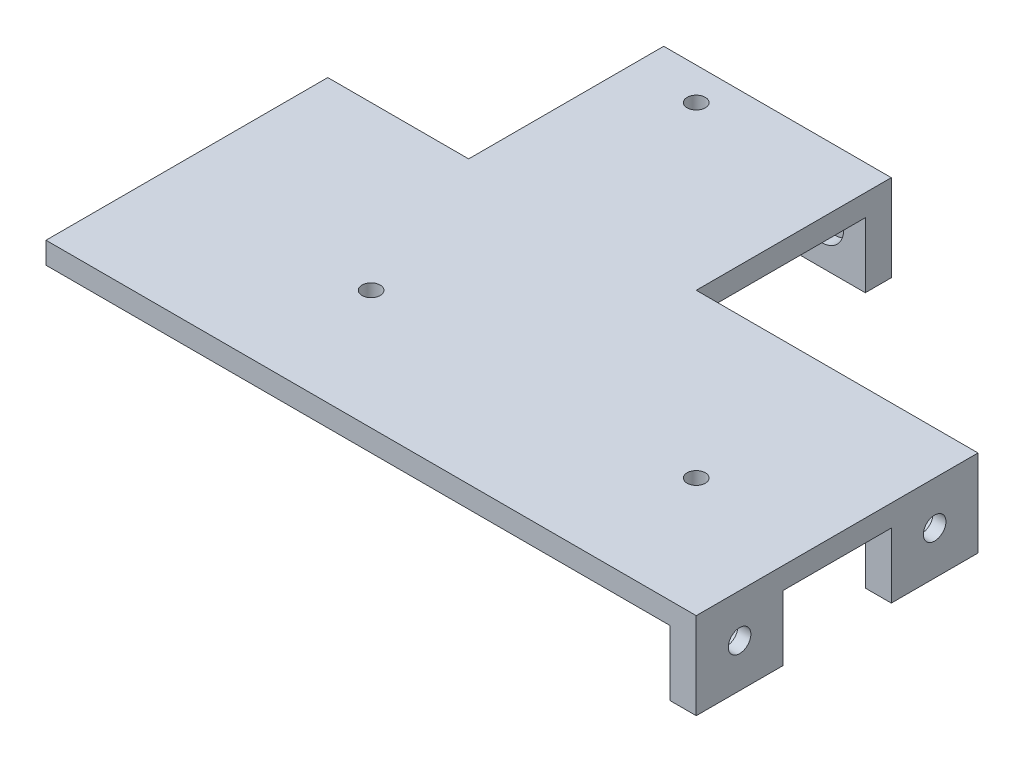
SolidWorks part; units mm, degrees
ref_plane "前视基准面" through (0, 0, 0) normal (0, 0, 1) x (1, 0, 0)
ref_plane "上视基准面" through (0, 0, 0) normal (0, 1, 0) x (1, 0, 0)
ref_plane "右视基准面" through (0, 0, 0) normal (1, 0, 0) x (0, 0, -1)
other "Configuration Table"
sketch "草图1" plane through (0, 0, 0) normal (0, 1, 0) x (1, 0, 0)
  line L6 (0, -65) -> (0, -130)
  line L7 (32.5, -65) -> (0, -65)
  line L15 (32.5, -20) -> (32.5, -65)
  line L18 (150, -130) -> (0, -130)
  line L20 (85, -20) -> (85, -65)
  line L21 (85, -20) -> (32.5, -20)
  line L24 (85, -65) -> (150, -65)
  line L25 (150, -65) -> (150, -130)
  circle A0 centre (47.5, -27.5) radius 2.1
  circle A2 centre (47.5, -102.5) radius 2.1
  circle A3 centre (122.5, -102.5) radius 2.1
extrude "凸台-拉伸1" add sketch "草图1" along normal blind 5
sketch "草图2" plane through (150, 0, 0) normal (1, 0, 0) x (0, 0, -1)
  line L1 (-65, 5) -> (-85, 5)
  line L2 (-65, 5) -> (-65, -15)
  line L3 (-65, -15) -> (-85, -15)
  line L4 (-85, 5) -> (-85, -15)
  circle A0 centre (-75, -5) radius 2.6
extrude "凸台-拉伸2" add sketch "草图2" against normal blind 6
sketch "草图3" plane through (144, 0, 0) normal (-1, 0, 0) x (0, 0, 1)
  circle A0 centre (75, -5) radius 5
extrude "切除-拉伸1" cut sketch "草图3" against normal blind 3
sketch "草图5" plane through (0, 0, 20) normal (0, 0, -1) x (-1, 0, 0)
  line L1 (-85, 5) -> (-65, 5)
  line L2 (-85, 5) -> (-85, -15)
  line L3 (-85, -15) -> (-65, -15)
  line L4 (-65, 5) -> (-65, -15)
  circle A0 centre (-75, -5) radius 2.6
extrude "凸台-拉伸3" add sketch "草图5" against normal blind 6
sketch "草图6" plane through (0, 0, 26) normal (0, 0, 1) x (1, 0, 0)
  circle A0 centre (75, -5) radius 5
extrude "切除-拉伸2" cut sketch "草图6" against normal blind 3
sketch "草图7" plane through (150, 0, 0) normal (1, 0, 0) x (0, 0, -1)
  line L1 (-130, 5) -> (-110, 5)
  line L2 (-130, 5) -> (-130, -15)
  line L3 (-130, -15) -> (-110, -15)
  line L4 (-110, 5) -> (-110, -15)
  circle A0 centre (-120, -5) radius 2.6
extrude "凸台-拉伸4" add sketch "草图7" against normal blind 6
sketch "草图8" plane through (144, 0, 0) normal (-1, 0, 0) x (0, 0, 1)
  circle A0 centre (120, -5) radius 5
extrude "切除-拉伸3" cut sketch "草图8" against normal blind 3
sketch "草图9" plane through (0, 0, 0) normal (0, -1, 0) x (1, 0, 0)
  circle A0 centre (47.5, 102.5) radius 5
  circle A1 centre (122.5, 102.5) radius 5
  circle A2 centre (47.5, 27.5) radius 5
  circle A3 centre (47.5, 102.5) radius 2.1
  circle A4 centre (122.5, 102.5) radius 2.1
  circle A5 centre (47.5, 27.5) radius 2.1
extrude "凸台-拉伸5" add sketch "草图9" along normal blind 7.6
sketch "草图10" plane through (0, -7.6, 0) normal (0, -1, 0) x (1, 0, 0)
  circle A0 centre (47.5, 102.5) radius 5
  circle A1 centre (47.5, 102.5) radius 3.95
  circle A2 centre (47.5, 27.5) radius 3.95
  circle A3 centre (47.5, 27.5) radius 5
  circle A4 centre (122.5, 102.5) radius 5
  circle A5 centre (122.5, 102.5) radius 3.95
extrude "凸台-拉伸6" add sketch "草图10" along normal blind 2.5
